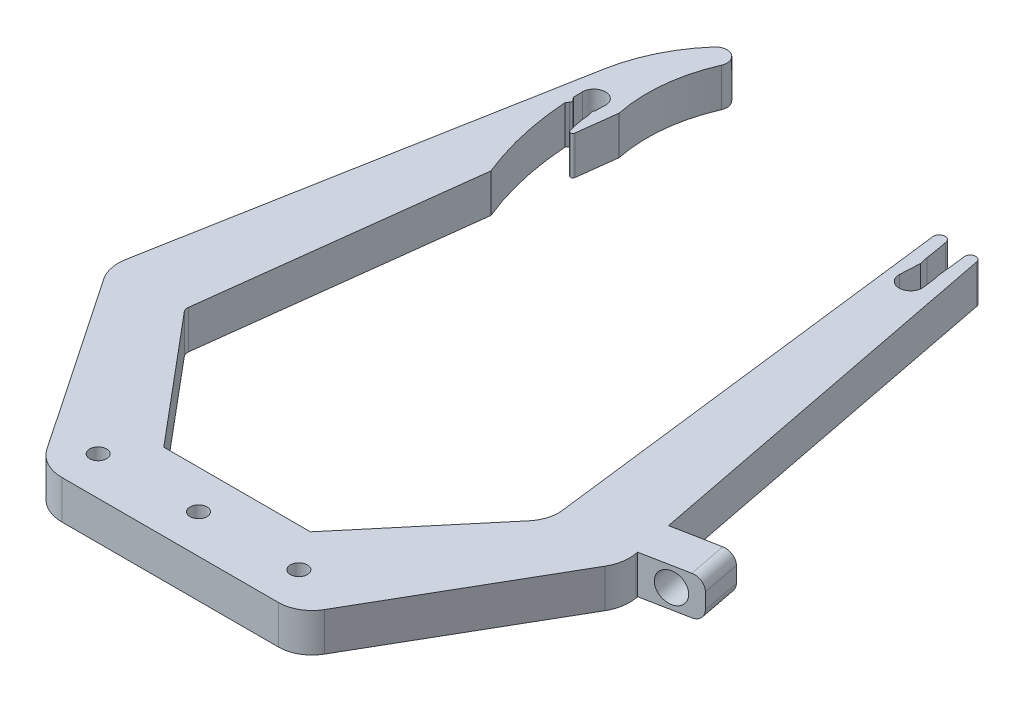
SolidWorks part; units mm, degrees
ref_plane "前视基准面" through (0, 0, 0) normal (0, 0, 1) x (1, 0, 0)
ref_plane "上视基准面" through (0, 0, 0) normal (0, 1, 0) x (1, 0, 0)
ref_plane "右视基准面" through (0, 0, 0) normal (1, 0, 0) x (0, 0, -1)
sketch "草图1" plane through (0, 0, 0) normal (0, 1, 0) x (1, 0, 0)
  line L0 (0, 0) -> (0, -20) construction
  line L1 (-19, 0) -> (19, 0)
  line L2 (-35.7227, -20) -> (35.7227, -20) construction
  line L3 (19, 0) -> (44.8546, 30.8123)
  line L4 (46.8223, 37.4552) -> (33.3895, 146.8562)
  line L5 (38.2306, -15.6563) -> (64.8605, 30.468)
  line L6 (66.0165, 37.3761) -> (44.728, 146.8959)
  line L9 (5.7071, -20) -> (30.7071, -20)
  line L11 (-5.7071, -20) -> (-25.3998, -20)
  line L12 (-35.7227, -20) -> (-64.8605, 30.468) construction
  line L13 (-19, 0) -> (-46.7237, 33.0398)
  line L14 (-47.2827, 33.706) -> (-33.3895, 146.8562) construction
  line L15 (-66.0165, 37.3761) -> (-46.8296, 141.8909)
  line L18 (-34.9739, 133.9531) -> (-47.1767, 34.5691)
  line L44 (-64.8605, 30.468) -> (-33.6816, -15.6046)
  line L45 (43.5031, 134.5037) -> (43.077, 137.8137)
  line L46 (42.1293, 145.1753) -> (42.8054, 138.9383)
  line L47 (42.8076, 138.9256) -> (43.077, 137.8137)
  line L48 (37.3208, 141.4732) -> (37.8151, 139.2584)
  line L49 (42.1293, 145.1753) -> (41.9652, 146.45)
  line L50 (37.8174, 139.2316) -> (37.5579, 134.1048)
  line L51 (-5.7071, -20) -> (5.7071, -20)
  arc A0 (64.8605, 30.468) -> (66.0165, 37.3761) centre (56.2002, 35.468) ccw
  arc A1 (-64.8605, 30.468) -> (-66.0165, 37.3761) centre (-56.2002, 35.468) cw
  arc A2 (33.3895, 146.8562) -> (36.3769, 147.1048) centre (34.8784, 147.039) cw
  arc A4 (37.5579, 134.1048) -> (43.5031, 134.5037) centre (40.5541, 133.9531) ccw
  arc A5 (44.728, 146.8959) -> (41.9652, 146.45) centre (43.3537, 146.6287) ccw
  arc A7 (-46.8296, 141.8909) -> (-37.4802, 161.1337) centre (-7.4871, 134.6684) cw
  arc A8 (-37.4802, 161.1337) -> (-32.4793, 157.9531) centre (-35.2307, 159.1488) cw
  arc A9 (-32.4793, 157.9531) -> (-34.9739, 133.9531) centre (4.2063, 142.0103) ccw
  arc A10 (-46.7237, 33.0398) -> (-47.1767, 34.5691) centre (-45.1916, 34.3254) cw
  arc A19 (38.2306, -15.6563) -> (30.7071, -20) centre (30.7071, -11.3127) cw
  arc A20 (44.8546, 30.8123) -> (46.8223, 37.4552) centre (38.1997, 36.3964) ccw
  arc A34 (-25.3998, -20) -> (-33.6816, -15.6046) centre (-25.3998, -10) cw
  arc A37 (42.8054, 138.9383) -> (42.8076, 138.9256) centre (42.9048, 138.9491) ccw
  arc A38 (37.8151, 139.2584) -> (37.8174, 139.2316) centre (37.7175, 139.2366) cw
  arc A39 (36.3769, 147.1048) -> (37.3208, 141.4732) centre (-54.0014, 129.0619) cw
  point P7 (0, 0)
  point P9 (0, -20)
  point P18 (66.7299, 33.706)
  point P24 (0, -19.5)
  point P43 (-30.7071, -20)
  point P50 (46.8296, 141.8909)
  point P53 (42.8061, 138.9319)
  point P76 (-42.7886, -7.7616)
  point P85 (47.2827, 33.706)
  point P88 (5.5, -20)
  point P91 (-5.5, -20)
  dimension "D14" = 10
  dimension "D17" = 1.5
  dimension "D18" = 3
  dimension "1.4" = 1.4
  dimension "D23" = 40
  dimension "D24" = 3
  dimension "D26" = 40
  dimension "D30" = 2
  dimension "D28" = 10
  dimension "D15" = 4.8
  dimension "D16" = 0.1
  dimension "D1" = 20
  dimension "D2" = 38
  dimension "D4" = 130
  dimension "D5" = 44
  dimension "D6" = 133
  dimension "D7" = 114
  dimension "D8" = 120
  dimension "D9" = 139
  dimension "D10" = 110
  dimension "D19" = 13
  dimension "D25" = 13
  dimension "D27" = 24
  dimension "D29" = 25
  dimension "D31" = 25
extrude "凸台-拉伸1" add sketch "草图1" along normal blind 10
sketch "草图2" plane through (0, 10, 0) normal (0, 1, 0) x (1, 0, 0)
  line L0 (-47.1767, 34.5691) -> (-34.9739, 133.9531) construction
  line L2 (-36.5496, 121.12) -> (-38.6077, 104.3574)
  line L4 (-38.7444, 130.4462) -> (-38.4867, 129.7939)
  line L9 (40.5541, 133.9531) -> (-57.9515, 133.9531) construction
  line L10 (0, 0) -> (0, -21.5487) construction
  line L11 (-38.5563, 131.3155) -> (-38.5461, 131.3251)
  line L12 (-44.4474, 131.5436) -> (-43.9248, 131.0031)
  line L13 (-43.8451, 129.9874) -> (-44.3325, 129.293)
  line L14 (38.654, -10) -> (-42.7555, -10) construction
  line L15 (19, 0) -> (-19, 0) construction
  arc A0 (-38.6077, 104.3574) -> (-44.3325, 129.293) centre (35.4981, 134.4958) cw
  circle A3 centre (0, -10) radius 2.2
  arc A7 (-38.5057, 133.7686) -> (-38.5563, 131.3155) centre (-8.5625, 131.9238) ccw
  arc A13 (-38.5057, 133.7686) -> (-44.4999, 133.932) centre (-41.5, 133.9531) ccw
  arc A14 (-44.4474, 131.5436) -> (-44.4999, 133.932) centre (35.4981, 134.4958) cw
  arc A15 (-38.4867, 129.7939) -> (-36.5496, 121.12) centre (-8.5625, 131.9238) ccw
  arc A16 (-38.5461, 131.3251) -> (-38.7444, 130.4462) centre (-38.0003, 130.7401) ccw
  arc A17 (-43.9248, 131.0031) -> (-43.8451, 129.9874) centre (-44.4999, 130.447) cw
  circle A18 centre (-26, -10) radius 2.2
  circle A19 centre (26, -10) radius 2.2
  point P30 (-38.9446, 130.9532)
  point P32 (-38.4181, 119.1092)
  point P34 (-43.4656, 130.5282)
  dimension "D5" = 3
  dimension "D6" = 30
  dimension "D7" = 80
  dimension "D9" = 4.4
  dimension "D11" = 26
  dimension "D12" = 0.8
  dimension "D14" = 10
  dimension "D2" = 4.4
  dimension "D3" = 4.4
  dimension "D4" = 41.5
  dimension "D13" = 26
extrude "切除-拉伸1" cut sketch "草图2" against normal up to next
fillet "圆角1" radius 0.6 2 edges at (-34.9739, 5, -133.9531) (-36.5496, 5, -121.12)
sketch "草图3" plane through (70.6136, 0, -13.7259) normal (0.9816, 0, -0.1908) x (-0.1908, 0, -0.9816)
  line L0 (24.0929, 10) -> (135.6625, 10) construction
  line L1 (24.5438, 10) -> (34.6883, 10)
  line L2 (24.5438, 10) -> (24.5438, 0)
  line L3 (24.5438, 0) -> (34.6883, 0)
  line L4 (34.6883, 10) -> (34.6883, 0)
  line L5 (24.0929, 0) -> (135.6625, 0) construction
extrude "凸台-拉伸2" add sketch "草图3" along normal blind 15
sketch "草图4" plane through (-4.6832, 0, -24.0929) normal (0.1908, 0, 0.9816) x (0.9816, 0, -0.1908)
  line L0 (86.9353, 5) -> (71.9353, 5) construction
  line L1 (86.9353, 10) -> (86.9353, 0) construction
  line L2 (71.9353, 10) -> (71.9353, 0) construction
  circle A0 centre (79.4353, 5) radius 3.8
  dimension "D1" = 7.6
extrude "切除-拉伸2" cut sketch "草图4" against normal up to next
fillet "圆角2" radius 3 2 edges at (79.687, 0, -45.66) (79.687, 10, -45.66)
